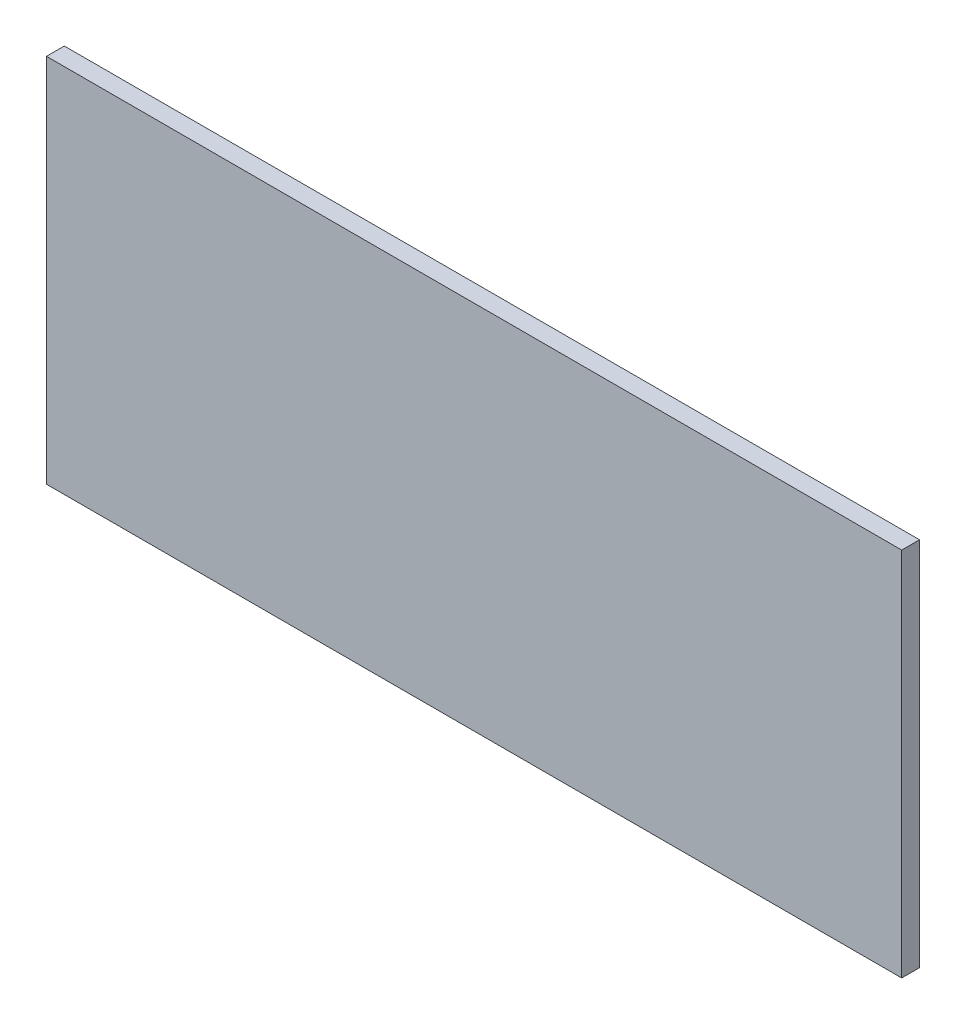
SolidWorks part; units mm, degrees
ref_plane "Front Plane" through (0, 0, 0) normal (0, 0, 1) x (1, 0, 0)
ref_plane "Top Plane" through (0, 0, 0) normal (0, 1, 0) x (1, 0, 0)
ref_plane "Right Plane" through (0, 0, 0) normal (1, 0, 0) x (0, 0, -1)
sketch "Sketch2" plane through (0, 0, 0) normal (0, 0, 1) x (1, 0, 0)
  line L1 (0, 0) -> (-152.4, 0)
  line L2 (0, 0) -> (0, 66.04)
  line L3 (0, 66.04) -> (-152.4, 66.04)
  line L4 (-152.4, 0) -> (-152.4, 66.04)
  dimension "D1" = 66.04
  dimension "D2" = 152.4
extrude "Boss-Extrude1" add sketch "Sketch2" along normal blind 3.175
